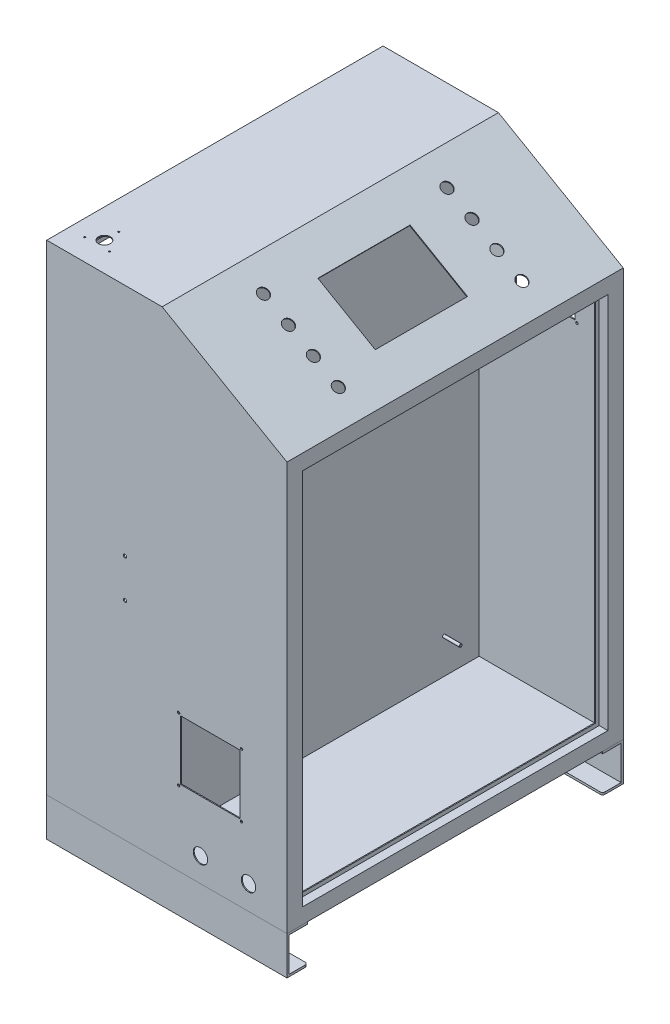
SolidWorks part; units mm, degrees
material "冷板"
ref_plane "前视基准面" through (0, 0, 0) normal (0, 0, 1) x (1, 0, 0)
ref_plane "上视基准面" through (0, 0, 0) normal (0, 1, 0) x (1, 0, 0)
ref_plane "右视基准面" through (0, 0, 0) normal (1, 0, 0) x (0, 0, -1)
sketch "草图1" plane through (0, 0, 0) normal (0, 0, 1) x (1, 0, 0)
  line L0 (0, 1252.3706) -> (0, 0) construction
  line L1 (0, 0) -> (879.6188, 0) construction
  line L2 (0, 0) -> (0, 1000)
  line L3 (0, 1000) -> (240.1924, 1000)
  line L4 (240.1924, 1000) -> (500, 850)
  line L5 (500, 850) -> (500, 0)
  line L6 (500, 0) -> (0, 0)
  line L7 (2, 2) -> (2, 998)
  line L8 (2, 998) -> (239.6565, 998)
  line L9 (239.6565, 998) -> (498, 848.8453)
  line L10 (498, 848.8453) -> (498, 2)
  line L11 (498, 2) -> (2, 2)
  dimension "D1" = 500
  dimension "D2" = 1000
  dimension "D3" = 850
  dimension "D4" = 150
  dimension "D5" = 2
extrude "凸台-拉伸1" add sketch "草图1" along normal mid plane 696
sketch "草图2" plane through (0, 0, 348) normal (0, 0, 1) x (1, 0, 0)
  line L5 (0, 0) -> (500, 0)
  line L6 (500, 0) -> (500, 850)
  line L7 (500, 850) -> (240.1924, 1000)
  line L8 (240.1924, 1000) -> (0, 1000)
  line L9 (0, 1000) -> (0, 0)
  line L10 (0, 0) -> (500, 0)
  line L11 (500, 0) -> (500, 850)
  line L12 (500, 850) -> (240.1924, 1000)
  line L13 (240.1924, 1000) -> (0, 1000)
  line L14 (0, 1000) -> (0, 0)
  dimension "D1" = 0
extrude "凸台-拉伸2" add sketch "草图2" along normal blind 2
sketch "草图3" plane through (0, 0, -348) normal (0, 0, -1) x (-1, 0, 0)
  line L5 (-500, 0) -> (0, 0)
  line L6 (0, 0) -> (0, 1000)
  line L7 (0, 1000) -> (-240.1924, 1000)
  line L8 (-240.1924, 1000) -> (-500, 850)
  line L9 (-500, 850) -> (-500, 0)
  line L10 (-500, 0) -> (0, 0)
  line L11 (0, 0) -> (0, 1000)
  line L12 (0, 1000) -> (-240.1924, 1000)
  line L13 (-240.1924, 1000) -> (-500, 850)
  line L14 (-500, 850) -> (-500, 0)
  dimension "D1" = 0
extrude "凸台-拉伸3" add sketch "草图3" along normal blind 2
sketch "草图4" plane through (500, 0, 0) normal (1, 0, 0) x (0, 0, -1)
  line L0 (0, 1153.4741) -> (0, 0) construction
  line L1 (-350, 0) -> (350, 0) construction
  line L2 (-320, 820) -> (320, 820)
  line L3 (-320, 820) -> (-320, 30)
  line L4 (-320, 30) -> (320, 30)
  line L5 (320, 820) -> (320, 30)
  line L6 (-350, 0) -> (-350, 850) construction
  line L7 (350, 850) -> (350, 0) construction
  line L8 (-350, 850) -> (350, 850) construction
  dimension "D1" = 30
  dimension "D2" = 30
  dimension "D3" = 30
  dimension "D4" = 30
extrude "切除-拉伸1" cut sketch "草图4" against normal blind 10
sketch "草图7" plane through (500, 0, 0) normal (1, 0, 0) x (0, 0, -1)
  line L0 (-318, 818) -> (318, 818)
  line L1 (-320, 820) -> (320, 820)
  line L2 (-320, 820) -> (-320, 30)
  line L3 (-320, 30) -> (320, 30)
  line L4 (320, 820) -> (320, 30)
  line L5 (318, 818) -> (318, 32)
  line L6 (-318, 32) -> (318, 32)
  line L7 (-318, 818) -> (-318, 32)
  dimension "D1" = 2
extrude "凸台-拉伸4" add sketch "草图7" against normal blind 18
sketch "草图8" plane through (0, 0, 0) normal (-1, 0, 0) x (0, 0, 1)
  line L8 (348, 998) -> (-348, 998)
  line L9 (-348, 998) -> (-348, 2)
  line L10 (-348, 2) -> (348, 2)
  line L11 (348, 2) -> (348, 998)
  line L12 (348, 998) -> (-348, 998)
  line L13 (-348, 998) -> (-348, 2)
  line L14 (-348, 2) -> (348, 2)
  line L15 (348, 2) -> (348, 998)
  dimension "D1" = 2
extrude "切除-拉伸2" cut sketch "草图8" against normal blind 10
sketch "草图9" plane through (482, 0, 0) normal (-1, 0, 0) x (0, 0, 1)
  line L0 (-310, 810) -> (310, 810)
  line L1 (-320, 820) -> (320, 820)
  line L2 (-320, 820) -> (-320, 30)
  line L3 (-320, 30) -> (320, 30)
  line L4 (320, 820) -> (320, 30)
  line L5 (310, 810) -> (310, 40)
  line L6 (-310, 40) -> (310, 40)
  line L7 (-310, 810) -> (-310, 40)
  dimension "D1" = 10
extrude "凸台-拉伸5" add sketch "草图9" along normal blind 2
sketch "草图10" plane through (0, 0, 0) normal (-1, 0, 0) x (0, 0, 1)
  line L1 (-348, 998) -> (348, 998)
  line L2 (-348, 998) -> (-348, 2)
  line L3 (-348, 2) -> (348, 2)
  line L4 (348, 998) -> (348, 2)
  line L6 (348, 998) -> (-348, 998) construction
  point P4 (0, 0)
  point P6 (-348, 998)
extrude "凸台-拉伸6" add sketch "草图10" against normal blind 2 from offset 200 separate body offset against normal yes
sketch "草图11" plane through (493.0608, 854.0064, 0) normal (0.5, 0.866, 0) x (0.866, -0.5, 0)
  line L0 (-291.9873, 0) -> (8.0127, 0) construction
  line L1 (-291.9873, -350) -> (-291.9873, 350) construction
  line L2 (8.0127, -350) -> (8.0127, 350) construction
  line L3 (-141.9873, 350) -> (-141.9873, -350) construction
  line L4 (-291.9873, 350) -> (8.0127, 350) construction
  line L5 (8.0127, -350) -> (-291.9873, -350) construction
  line L7 (-210.9873, 96) -> (-72.9873, 96)
  line L8 (-210.9873, 96) -> (-210.9873, -96)
  line L9 (-210.9873, -96) -> (-72.9873, -96)
  line L10 (-72.9873, 96) -> (-72.9873, -96)
  dimension "D1" = 138
  dimension "D2" = 192
extrude "切除-拉伸3" cut sketch "草图11" against normal blind 10
sketch "草图12" plane through (500, 0, 0) normal (1, 0, 0) x (0, 0, -1)
  line L0 (-350, 0) -> (-350, -80)
  line L1 (-350, -80) -> (-307, -80)
  line L2 (-350, 0) -> (-307, 0)
  line L3 (-350, 0) -> (350, 0) construction
  line L4 (-345.5, -4.5) -> (-307, -4.5)
  line L5 (-345.5, -4.5) -> (-345.5, -75.5)
  line L6 (-345.5, -75.5) -> (-307, -75.5)
  line L7 (-307, 0) -> (-307, -4.5)
  line L8 (-307, -75.5) -> (-307, -80)
  line L9 (0, 0) -> (0, -219.6387) construction
  line L10 (307, -75.5) -> (307, -80)
  line L11 (307, 0) -> (307, -4.5)
  line L12 (345.5, -75.5) -> (307, -75.5)
  line L13 (345.5, -4.5) -> (345.5, -75.5)
  line L14 (345.5, -4.5) -> (307, -4.5)
  line L15 (350, 0) -> (307, 0)
  line L16 (350, -80) -> (307, -80)
  line L17 (350, 0) -> (350, -80)
  dimension "D1" = 80
  dimension "D2" = 43
  dimension "D3" = 43
  dimension "D4" = 4.5
extrude "凸台-拉伸7" add sketch "草图12" against normal up to surface (500 mm away) separate body up to face at (0, 500, 0)
sketch "草图13" plane through (493.0608, 854.0064, 0) normal (0.5, 0.866, 0) x (0.866, -0.5, 0)
  line L0 (-141.9873, 96) -> (-141.9873, -96) construction
  line L1 (-72.9873, 96) -> (-210.9873, 96) construction
  line L2 (-210.9873, -96) -> (-72.9873, -96) construction
  line L3 (-141.9873, 96) -> (-141.9873, 232.7907) construction
  line L4 (-231.9873, 191) -> (-171.9873, 191) construction
  line L6 (-51.9873, 191) -> (-111.9873, 191) construction
  line L7 (0, 0) -> (-427.934, 0) construction
  circle A0 centre (-171.9873, 191) radius 11.25
  circle A1 centre (-231.9873, 191) radius 11.25
  circle A2 centre (-51.9873, 191) radius 11.25
  circle A3 centre (-111.9873, 191) radius 11.25
  dimension "D1" = 22.5
  dimension "D2" = 60
  dimension "D3" = 60
  dimension "D4" = 95
extrude "切除-拉伸4" cut sketch "草图13" against normal blind 10
sketch "草图23" plane through (0, 0, 350) normal (0, 0, 1) x (1, 0, 0)
  line L0 (500, 0) -> (500, 850) construction
  line L1 (0, 0) -> (500, 0) construction
  line L2 (420, 50) -> (320, 50) construction
  circle A0 centre (420, 50) radius 15
  circle A1 centre (320, 50) radius 15
  point P9 (77.0058, 50)
  dimension "D1" = 30
  dimension "D2" = 80
  dimension "D3" = 50
  dimension "D4" = 100
extrude "切除-拉伸8" cut sketch "草图23" against normal blind 10
sketch "草图29" plane through (0, 0, -350) normal (0, 0, -1) x (-1, 0, 0)
  line L0 (-340, 152.5) -> (-340, 944.8531) construction
  line L1 (-340, 770) -> (-219.7051, 770) construction
  line L4 (-500, 850) -> (-500, 0) construction
  line L5 (0, -80) -> (-500, -80) construction
  line L6 (-402, 832) -> (-278, 832)
  line L7 (-402, 832) -> (-402, 708)
  line L8 (-402, 708) -> (-278, 708)
  line L9 (-278, 832) -> (-278, 708)
  line L10 (-402, 832) -> (-278, 708) construction
  line L11 (-402, 708) -> (-278, 832) construction
  circle A1 centre (-274.5, 835.5) radius 2.5
  circle A2 centre (-274.5, 704.5) radius 2.5
  circle A3 centre (-405.5, 835.5) radius 2.5
  circle A4 centre (-405.5, 704.5) radius 2.5
  point P18 (-405.5, 730.3587)
  dimension "D1" = 124
  dimension "D2" = 124
  dimension "D3" = 131
  dimension "D4" = 131
  dimension "D5" = 5
  dimension "D6" = 160
  dimension "D7" = 850
extrude "切除-拉伸13" cut sketch "草图29" against normal blind 10
sketch "草图31" plane through (0, 1000, 0) normal (0, 1, 0) x (1, 0, 0)
  line L0 (240.1924, -350) -> (0, -350) construction
  line L3 (0, -350) -> (0, 350) construction
  circle A3 centre (60, -290) radius 12.5
  point P0 (0, 0)
  dimension "D1" = 60
  dimension "D2" = 60
  dimension "D7" = 25
extrude "切除-拉伸16" cut sketch "草图31" against normal blind 10
sketch "草图34" plane through (0, 0, 0) normal (-1, 0, 0) x (0, 0, 1)
  line L0 (-320, 970) -> (320, 970)
  line L1 (-348, 998) -> (348, 998)
  line L2 (-348, 998) -> (-348, 2)
  line L3 (-348, 2) -> (348, 2)
  line L4 (348, 998) -> (348, 2)
  line L5 (320, 970) -> (320, 30)
  line L6 (-320, 30) -> (320, 30)
  line L7 (-320, 970) -> (-320, 30)
  dimension "D1" = 28
extrude "凸台-拉伸10" add sketch "草图34" against normal blind 2
sketch "草图36" plane through (0, 0, 0) normal (-1, 0, 0) x (0, 0, 1)
  line L0 (-318, 968) -> (318, 968)
  line L1 (-320, 970) -> (320, 970)
  line L2 (-320, 970) -> (-320, 30)
  line L3 (-320, 30) -> (320, 30)
  line L4 (320, 970) -> (320, 30)
  line L5 (318, 968) -> (318, 32)
  line L6 (-318, 32) -> (318, 32)
  line L7 (-318, 968) -> (-318, 32)
  dimension "D1" = 2
extrude "凸台-拉伸11" add sketch "草图36" against normal blind 18
sketch "草图37" plane through (18, 0, 0) normal (1, 0, 0) x (0, 0, -1)
  line L0 (310, 960) -> (-310, 960)
  line L1 (318, 968) -> (-318, 968)
  line L2 (318, 968) -> (318, 32)
  line L3 (318, 32) -> (-318, 32)
  line L4 (-318, 968) -> (-318, 32)
  line L5 (-310, 960) -> (-310, 40)
  line L6 (310, 40) -> (-310, 40)
  line L7 (310, 960) -> (310, 40)
  line L8 (-318, 32) -> (-318, 968) construction
  line L9 (318, 32) -> (-318, 32) construction
  point P10 (0, 0)
  point P11 (-318, 32)
  point P16 (318, 968)
  point P17 (318, 968)
  dimension "D1" = 8
extrude "凸台-拉伸12" add sketch "草图37" along normal blind 2 separate body
fillet "圆角1" radius 5 2 edges at (0, -77.75, 307) (500, -77.75, 307)
fillet "圆角2" radius 5 2 edges at (500, -77.75, -307) (0, -77.75, -307)
mirror "镜向1" about plane through (0, 0, 0) normal (0, 0, 1) of "切除-拉伸4"
sketch "草图41" plane through (0, 0, 350) normal (0, 0, 1) x (1, 0, 0)
  line L1 (274.5, 285.5) -> (405.5, 285.5) construction
  line L2 (274.5, 285.5) -> (274.5, 154.5) construction
  line L3 (274.5, 154.5) -> (405.5, 154.5) construction
  line L4 (405.5, 285.5) -> (405.5, 154.5) construction
  line L5 (274.5, 285.5) -> (405.5, 154.5) construction
  line L6 (274.5, 154.5) -> (405.5, 285.5) construction
  line L8 (0, -80) -> (500, -80) construction
  line L9 (278, 282) -> (402, 282)
  line L10 (278, 282) -> (278, 158)
  line L11 (278, 158) -> (402, 158)
  line L12 (402, 282) -> (402, 158)
  line L13 (278, 282) -> (402, 158) construction
  line L14 (278, 158) -> (402, 282) construction
  line L15 (500, 0) -> (500, 850) construction
  circle A1 centre (274.5, 285.5) radius 2.5
  circle A2 centre (274.5, 154.5) radius 2.5
  circle A3 centre (405.5, 154.5) radius 2.5
  circle A4 centre (405.5, 285.5) radius 2.5
  point P0 (340, 220)
  dimension "D1" = 124
  dimension "D5" = 5
  dimension "D2" = 131
  dimension "D3" = 131
  dimension "D4" = 124
  dimension "D6" = 300
  dimension "D7" = 160
extrude "切除-拉伸21" cut sketch "草图41" against normal blind 10
sketch "草图42" plane through (202, 0, 0) normal (1, 0, 0) x (0, 0, -1)
  line L0 (0, 2) -> (0, 998) construction
  line L1 (348, 2) -> (-348, 2) construction
  line L2 (-348, 998) -> (348, 998) construction
  line L4 (-275, 925) -> (275, 925) construction
  line L5 (-275, 925) -> (-275, 75) construction
  line L6 (-275, 75) -> (275, 75) construction
  line L7 (275, 925) -> (275, 75) construction
  line L8 (-275, 925) -> (275, 75) construction
  line L9 (-275, 75) -> (275, 925) construction
  circle A0 centre (-275, 925) radius 3
  circle A1 centre (275, 925) radius 3
  circle A2 centre (-275, 75) radius 3
  circle A3 centre (275, 75) radius 3
  point P6 (0, 500)
  dimension "D1" = 6
  dimension "D2" = 550
  dimension "D3" = 850
extrude "凸台-拉伸13" add sketch "草图42" along normal blind 35
cosmetic thread "装饰螺纹线1" parameters "D2"=4.891
cosmetic thread "装饰螺纹线2" parameters "D2"=4.891
cosmetic thread "装饰螺纹线3" parameters "D2"=4.891
cosmetic thread "装饰螺纹线4" parameters "D2"=4.891
chamfer "倒角1" distance 0.5 angle 45 4 edges at (237, 928, 275) (237, 928, -275) (237, 78, -275) (237, 78, 275)
hole_wizard "M4 螺纹孔1" positions "草图43" profile "草图44" tap size "M4" standard "GB"
sketch "草图43" plane through (0, 1000, 0) normal (0, 1, 0) x (1, 0, 0)
  line L0 (60, -290) -> (60, -260) construction
  line L3 (60, -290) -> (34.0192, -305) construction
  line L6 (60, -290) -> (85.9808, -305) construction
  point P2 (60, -260)
  point P9 (34.0192, -305)
  point P14 (85.9808, -305)
  dimension "D1" = 30
  dimension "D2" = 120
  dimension "D3" = 120
sketch "草图44" plane through (85.9808, 1000, 305) normal (1, 0, 0) x (0, 0, 1)
  line L0 (0, 0) -> (0, 11.0914)
  line L1 (0, 11.0914) -> (1.65, 10.1)
  line L2 (1.65, 10.1) -> (1.65, 0)
  line L5 (1.65, 0) -> (0, 0)
  line L10 (0, 11.0914) -> (-1.65, 10.1) construction
  line L11 (0, -6.35) -> (0, 107.95) construction
  dimension "螺纹孔钻头直径" = 3.3
  dimension "螺纹孔钻头深度" = 10.1
  dimension "导头角度" = 118
cosmetic thread "孔螺蚊线20" parameters "D1"=2, "D2"=4
cosmetic thread "孔螺蚊线21" parameters "D1"=2, "D2"=4
cosmetic thread "孔螺蚊线22" parameters "D1"=2, "D2"=4
hole_wizard "M8 螺纹孔1" positions "草图45" profile "草图46" tap size "M8" standard "GB"
sketch "草图45" plane through (0, 0, 350) normal (0, 0, 1) x (1, 0, 0)
  line L0 (163, 507.5) -> (163, 516.5) construction
  line L1 (158.5, 507.5) -> (167.5, 507.5) construction
  line L2 (167.5, 516.5) -> (158.5, 516.5) construction
  line L3 (163, 427.5) -> (163, 436.5) construction
  line L4 (167.5, 427.5) -> (158.5, 427.5) construction
  line L5 (167.5, 436.5) -> (158.5, 436.5) construction
  point P12 (163, 512)
  point P24 (163, 432)
sketch "草图46" plane through (163, 432, 350) normal (1, 0, 0) x (0, -1, 0)
  line L0 (0, 0) -> (0, 21.7929)
  line L1 (0, 21.7929) -> (3.4, 19.75)
  line L2 (3.4, 19.75) -> (3.4, 0)
  line L5 (3.4, 0) -> (0, 0)
  line L10 (0, 21.7929) -> (-3.4, 19.75) construction
  line L11 (0, -6.35) -> (0, 107.95) construction
  dimension "螺纹孔钻头直径" = 6.8
  dimension "螺纹孔钻头深度" = 19.75
  dimension "导头角度" = 118
cosmetic thread "孔螺蚊线23" parameters "D1"=2, "D2"=8
cosmetic thread "孔螺蚊线24" parameters "D1"=2, "D2"=8
